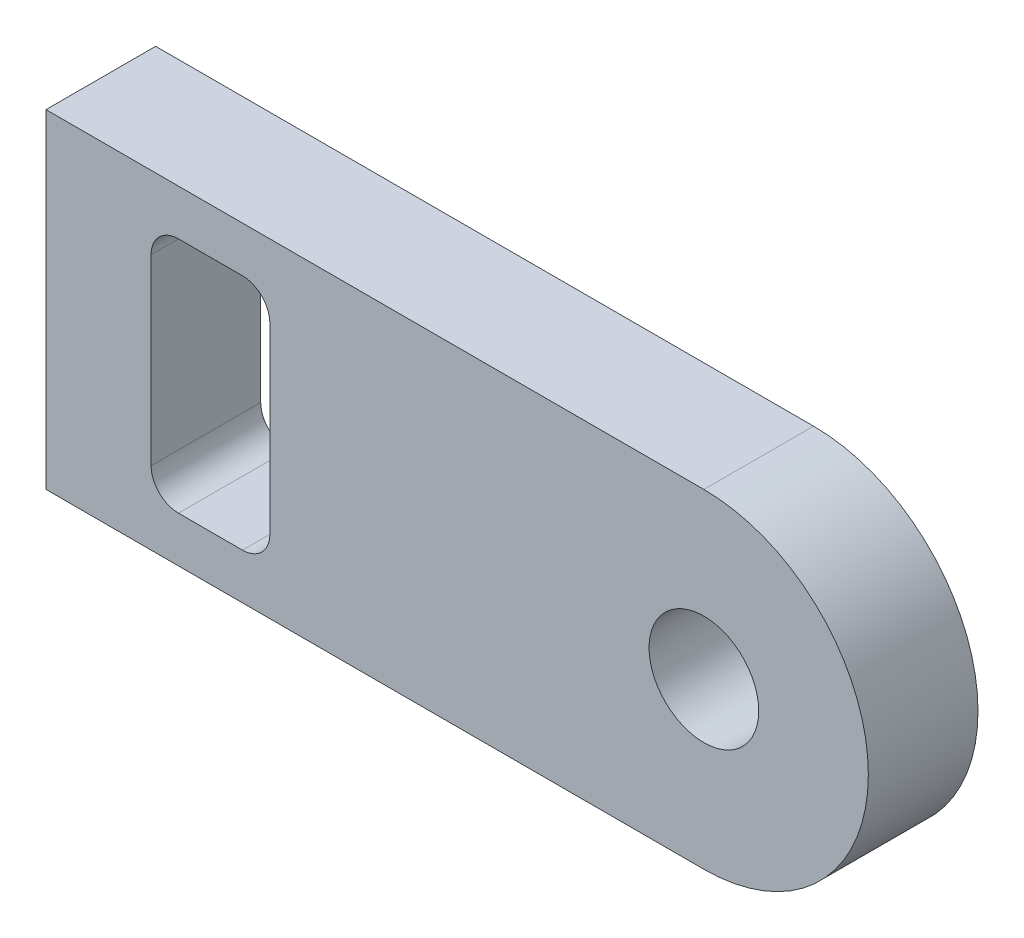
SolidWorks part; units mm, degrees
ref_plane "Alzado" through (0, 0, 0) normal (0, 0, 1) x (1, 0, 0)
ref_plane "Planta" through (0, 0, 0) normal (0, 1, 0) x (1, 0, 0)
ref_plane "Vista lateral" through (0, 0, 0) normal (1, 0, 0) x (0, 0, -1)
sketch "Model" plane through (0, 0, 0) normal (0, 0, 1) x (1, 0, 0)
  line L0 (183.0979, 273.6465) -> (201.0979, 273.6465)
  line L1 (183.0979, 264.6465) -> (183.0979, 273.6465)
  line L2 (201.0979, 264.6465) -> (183.0979, 264.6465)
  line L3 (186.7229, 265.8965) -> (188.4729, 265.8965)
  line L4 (189.2229, 266.6465) -> (189.2229, 271.6465)
  line L5 (188.4729, 272.3965) -> (186.7229, 272.3965)
  line L6 (185.9729, 271.6465) -> (185.9729, 266.6465)
  arc A0 (201.0979, 264.6465) -> (201.0979, 273.6465) centre (201.0979, 269.1465) ccw
  circle A1 centre (201.0979, 269.1465) radius 1.5
  arc A2 (185.9729, 266.6465) -> (186.7229, 265.8965) centre (186.7229, 266.6465) ccw
  arc A3 (188.4729, 265.8965) -> (189.2229, 266.6465) centre (188.4729, 266.6465) ccw
  arc A4 (189.2229, 271.6465) -> (188.4729, 272.3965) centre (188.4729, 271.6465) ccw
  arc A5 (186.7229, 272.3965) -> (185.9729, 271.6465) centre (186.7229, 271.6465) ccw
extrude "Saliente-Extruir1" add sketch "Model" along normal blind 3
